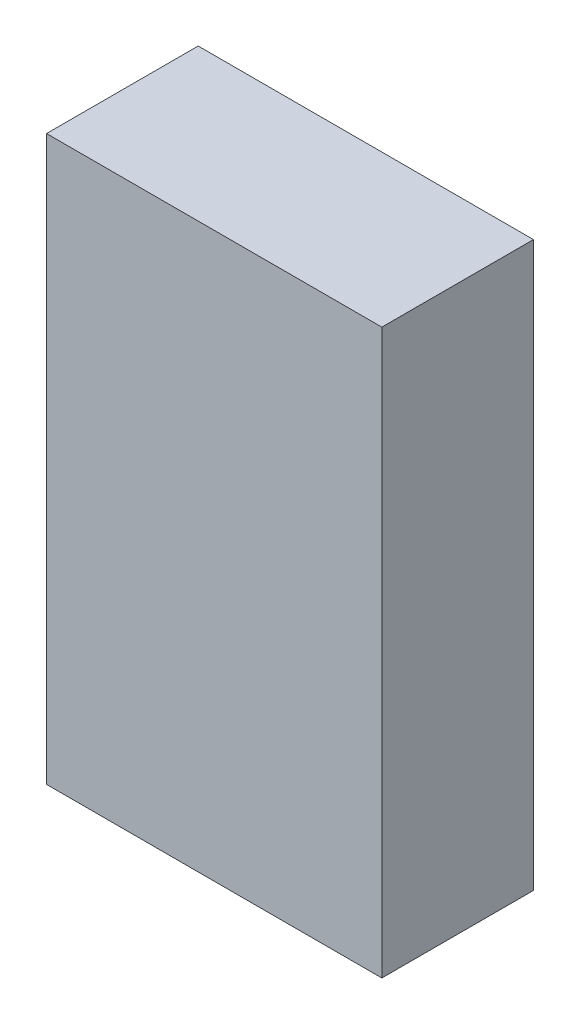
SolidWorks part; units mm, degrees
ref_plane "Front Plane" through (0, 0, 0) normal (0, 0, 1) x (1, 0, 0)
ref_plane "Top Plane" through (0, 0, 0) normal (0, 1, 0) x (1, 0, 0)
ref_plane "Right Plane" through (0, 0, 0) normal (1, 0, 0) x (0, 0, -1)
sketch "Sketch1" plane through (0, 0, 0) normal (0, 0, 1) x (1, 0, 0)
  line L1 (-17.25, -29) -> (17.25, -29)
  line L2 (-17.25, -29) -> (-17.25, 29)
  line L3 (-17.25, 29) -> (17.25, 29)
  line L4 (17.25, -29) -> (17.25, 29)
  line L5 (-17.25, -29) -> (17.25, 29) construction
  line L6 (-17.25, 29) -> (17.25, -29) construction
  point P0 (0, 0)
extrude "Envelope" add sketch "Sketch1" along normal blind 15.6
